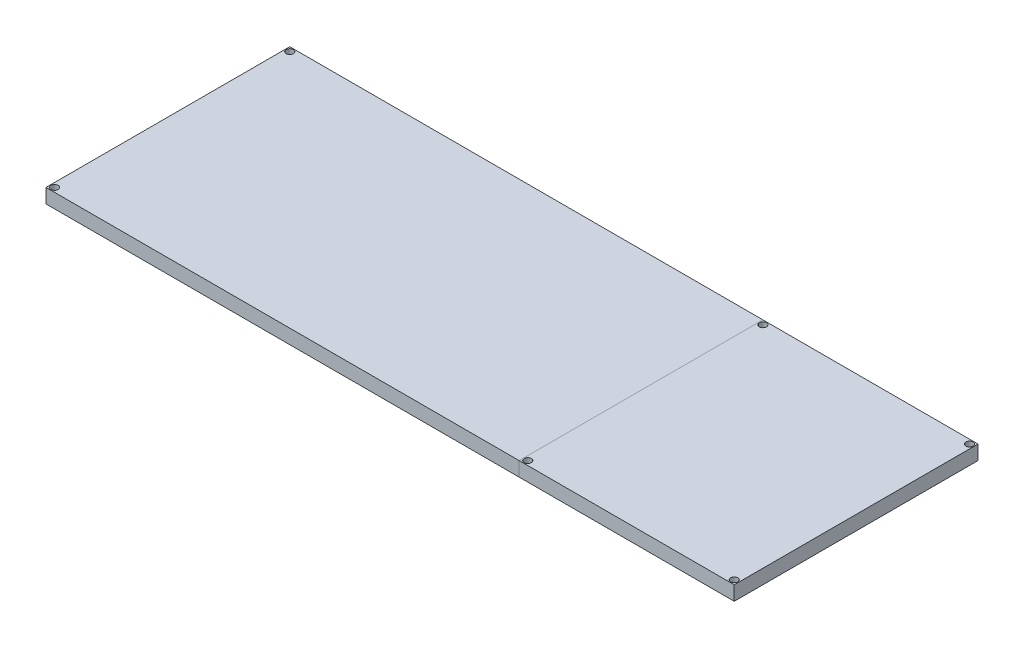
SolidWorks part; units mm, degrees
material "ABS"
ref_plane "Ön Düzlem" through (0, 0, 0) normal (0, 0, 1) x (1, 0, 0)
ref_plane "Üst Düzlem" through (0, 0, 0) normal (0, 1, 0) x (1, 0, 0)
ref_plane "Sağ Düzlem" through (0, 0, 0) normal (1, 0, 0) x (0, 0, -1)
sketch "Çizim1" plane through (0, 0, 0) normal (0, 1, 0) x (1, 0, 0)
  line L1 (0, 0) -> (75, 0)
  line L2 (0, 0) -> (0, 85)
  line L3 (0, 85) -> (75, 85)
  line L4 (75, 0) -> (75, 85)
  dimension "D1" = 85
  dimension "D2" = 75
extrude "Yükseklik-Ekstrüzyon1" add sketch "Çizim1" along normal blind 5 contours L2 L3 L4 L1
sketch "Çizim2" plane through (0, 0, 0) normal (-1, 0, 0) x (0, 0, 1)
  line L1 (-85, 5) -> (0, 5)
  line L2 (-85, 5) -> (-85, 0)
  line L3 (-85, 0) -> (0, 0)
  line L4 (0, 5) -> (0, 0)
extrude "Yükseklik-Ekstrüzyon3" add sketch "Çizim2" along normal blind 165 separate body
sketch "Çizim3" plane through (0, 5, 0) normal (0, 1, 0) x (1, 0, 0)
  line L0 (0, 85) -> (0, 0) construction
  line L1 (0, 0) -> (75, 0) construction
  line L2 (75, 0) -> (75, 85) construction
  line L3 (75, 85) -> (0, 85) construction
  circle A0 centre (1.5, 1.5) radius 1.25
  circle A1 centre (73.5, 1.5) radius 1.25
  circle A2 centre (73.5, 83.5) radius 1.25
  circle A3 centre (1.5, 83.5) radius 1.25
  dimension "D3" = 2.5
  dimension "D7" = 1.5
  dimension "D1" = 1.5
  dimension "D2" = 1.5
  dimension "D6" = 1.5
  dimension "D8" = 1.5
  dimension "D4" = 2
  dimension "D5" = 2
extrude "Kes-Ekstrüzyon1" cut sketch "Çizim3" against normal through all
sketch "Çizim4" plane through (0, 5, 0) normal (0, 1, 0) x (1, 0, 0)
  line L0 (-165, 0) -> (-165, 85) construction
  line L1 (-165, 0) -> (0, 0) construction
  line L2 (-165, 85) -> (0, 85) construction
  circle A0 centre (-163.5, 1.5) radius 1.25
  circle A1 centre (-163.5, 83.5) radius 1.25
  dimension "D1" = 2.5
  dimension "D2" = 1.5
  dimension "D3" = 1.5
  dimension "D5" = 1.5
  dimension "D4" = 2
extrude "Kes-Ekstrüzyon2" cut sketch "Çizim4" against normal through all
